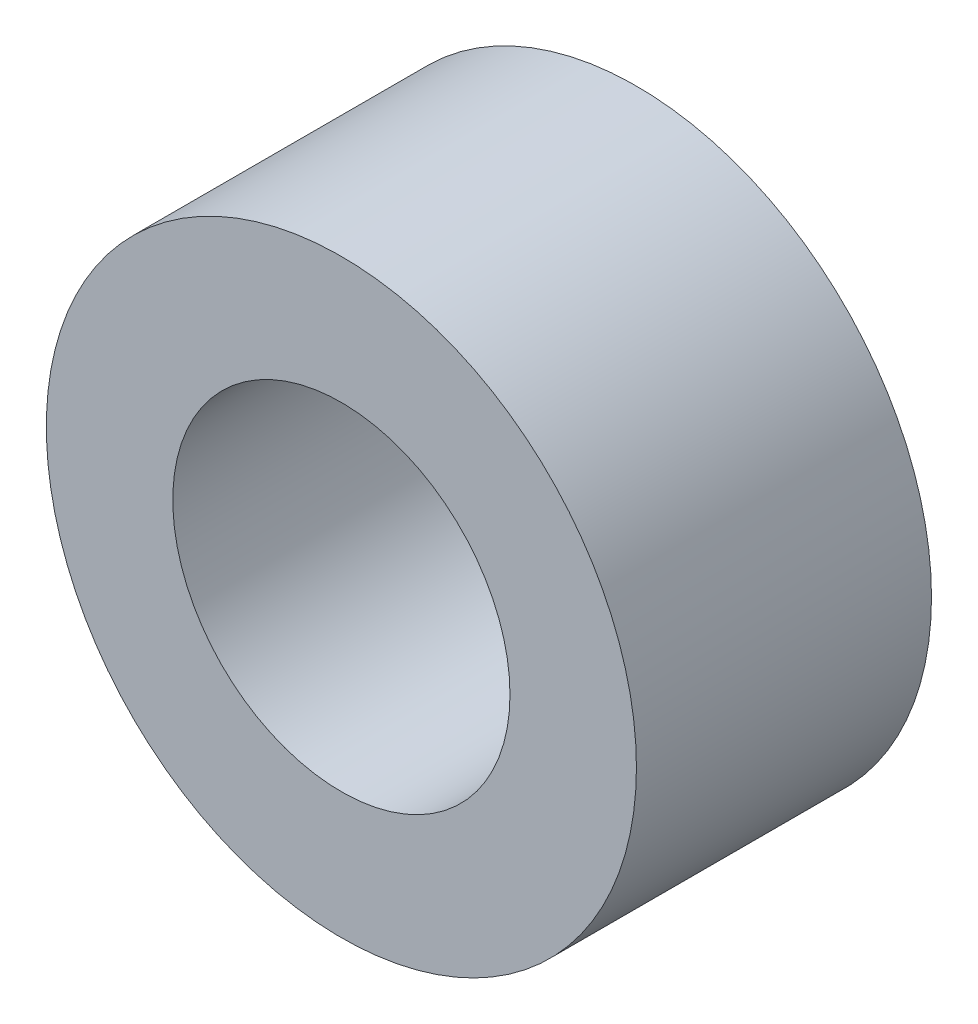
SolidWorks part; units mm, degrees
ref_plane "前视基准面" through (0, 0, 0) normal (0, 0, 1) x (1, 0, 0)
ref_plane "上视基准面" through (0, 0, 0) normal (0, 1, 0) x (1, 0, 0)
ref_plane "右视基准面" through (0, 0, 0) normal (1, 0, 0) x (0, 0, -1)
sketch "草图1" plane through (0, 0, 0) normal (0, 0, 1) x (1, 0, 0)
  circle A0 centre (0, 0) radius 20
  circle A1 centre (0, 0) radius 35
  dimension "D1" = 40
  dimension "D2" = 70
extrude "凸台-拉伸1" add sketch "草图1" along normal blind 35
